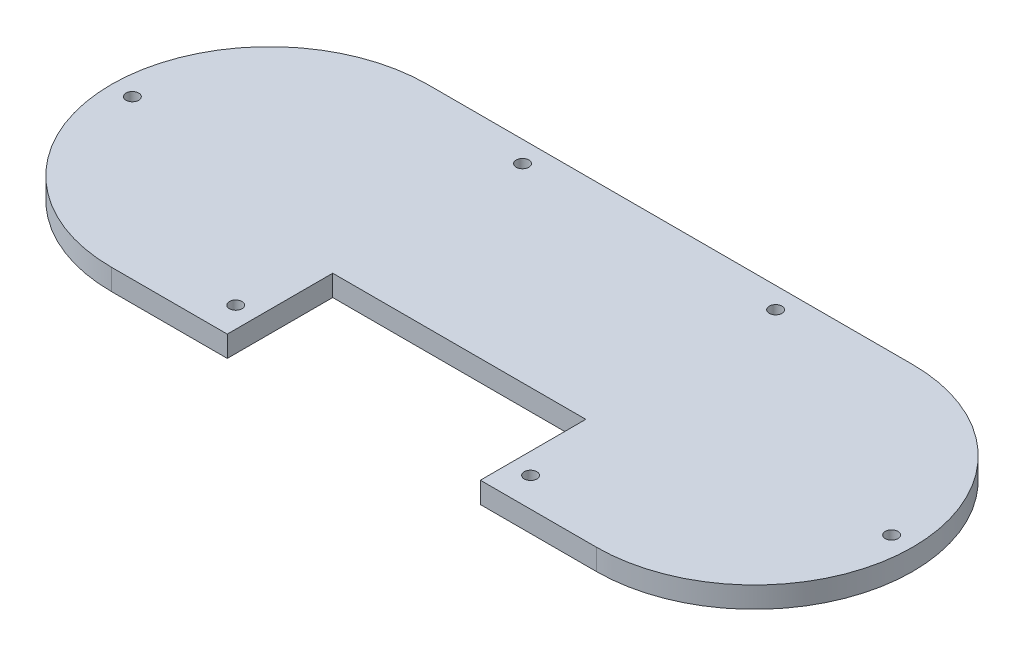
SolidWorks part; units mm, degrees
ref_plane "Front Plane" through (0, 0, 0) normal (0, 0, 1) x (1, 0, 0)
ref_plane "Top Plane" through (0, 0, 0) normal (0, 1, 0) x (1, 0, 0)
ref_plane "Right Plane" through (0, 0, 0) normal (1, 0, 0) x (0, 0, -1)
sketch "Sketch1" plane through (0, 0, 0) normal (0, 1, 0) x (1, 0, 0)
  line L0 (-57.5, 0) -> (57.5, 0) construction
  line L1 (-57.5, 37.5) -> (57.5, 37.5)
  line L2 (-57.5, -37.5) -> (-30, -37.5)
  line L3 (-57.5, 0) -> (-95, 0) construction
  line L4 (57.5, 0) -> (95, 0) construction
  line L5 (-30, -37.5) -> (-30, -12.5)
  line L6 (-30, -12.5) -> (30, -12.5)
  line L7 (30, -12.5) -> (30, -37.5)
  line L8 (0, 0) -> (0, -12.5) construction
  line L9 (30, -37.5) -> (57.5, -37.5)
  line L10 (-40, -35.5) -> (-30, -35.5) construction
  line L11 (-34.9497, -30.5503) -> (-34.9497, -37.5) construction
  line L12 (34.9497, -30.5503) -> (-34.9497, -30.5503) construction
  line L13 (-40, -35.5) -> (-40, -37.5) construction
  line L14 (-30, -35.5) -> (-34.9497, -30.5503) construction
  line L15 (30, -12.5) -> (30, 32.5) construction
  line L16 (30, 32.5) -> (30, 37.5) construction
  line L17 (30, 32.5) -> (-30, 32.5) construction
  line L18 (-30, 32.5) -> (-30, -12.5) construction
  line L19 (-34.9497, -30.5503) -> (-37.0711, -28.4289) construction
  line L20 (34.9497, -30.5503) -> (34.9497, -37.5) construction
  line L21 (0, -30.5503) -> (0, -12.5) construction
  arc A0 (-57.5, 37.5) -> (-57.5, -37.5) centre (-57.5, 0) ccw
  arc A1 (57.5, -37.5) -> (57.5, 37.5) centre (57.5, 0) ccw
  circle A2 centre (-90, 0) radius 1.5
  circle A3 centre (-30, 32.5) radius 1.5
  circle A4 centre (30, 32.5) radius 1.5
  circle A5 centre (90, 0) radius 1.5
  circle A6 centre (34.9497, -30.5503) radius 1.5
  circle A7 centre (-34.9497, -30.5503) radius 1.5
  arc A8 (-40, -35.5) -> (-30, -25.5) centre (-30, -35.5) cw construction
  point P3 (0, 0)
  dimension "D5" = 3
  dimension "D6" = 10
  dimension "D1" = 75
  dimension "D2" = 190
  dimension "D3" = 60
  dimension "D4" = 25
  dimension "D7" = 5
  dimension "D8" = 5
  dimension "D9" = 3
  dimension "D10" = 5
  dimension "D11" = 2
extrude "Boss-Extrude1" add sketch "Sketch1" along normal blind 5 contours L5 L6 L7 L9 A1 L1 A0 L2 | A7 | A2 | A3 | A4 | A5 | A6
